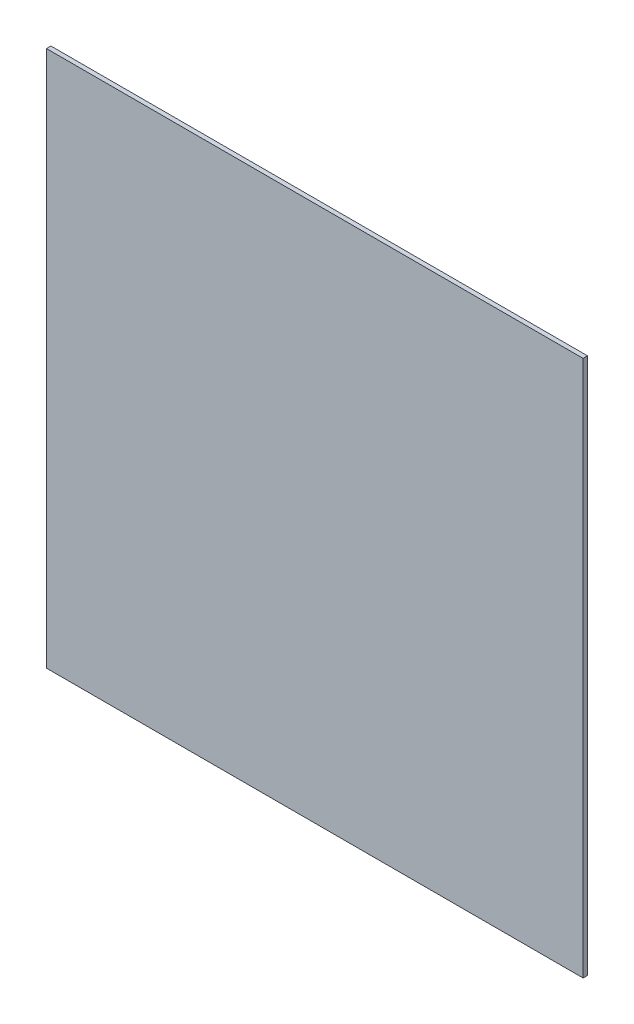
SolidWorks part; units mm, degrees
ref_plane "Front Plane" through (0, 0, 0) normal (0, 0, 1) x (1, 0, 0)
ref_plane "Top Plane" through (0, 0, 0) normal (0, 1, 0) x (1, 0, 0)
ref_plane "Right Plane" through (0, 0, 0) normal (1, 0, 0) x (0, 0, -1)
sketch "Sketch1" plane through (0, 0, 0) normal (0, 0, 1) x (1, 0, 0)
  line L8 (-60.5, -60.5) -> (60.5, -60.5)
  line L9 (60.5, -60.5) -> (60.5, 60.5)
  line L10 (60.5, 60.5) -> (-60.5, 60.5)
  line L11 (-60.5, 60.5) -> (-60.5, -60.5)
extrude "Boss-Extrude1" add sketch "Sketch1" along normal blind 1
